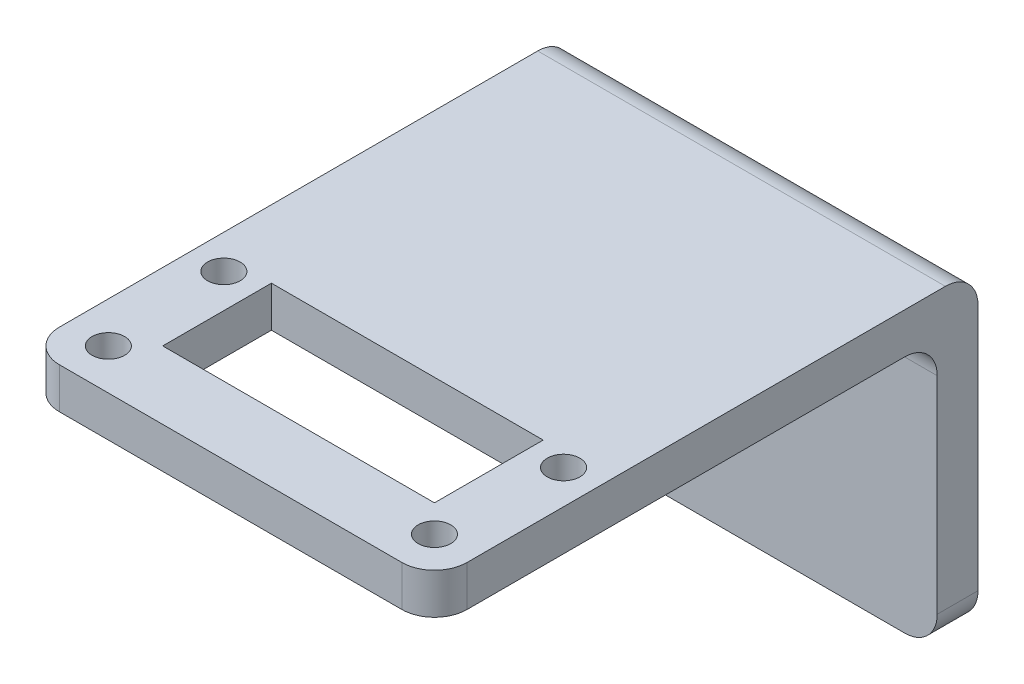
SolidWorks part; units mm, degrees
ref_plane "Plano frontal" through (0, 0, 0) normal (0, 0, 1) x (1, 0, 0)
ref_plane "Plano superior" through (0, 0, 0) normal (0, 1, 0) x (1, 0, 0)
ref_plane "Plano direito" through (0, 0, 0) normal (1, 0, 0) x (0, 0, -1)
sketch "Esboço1" plane through (0, 0, 0) normal (0, 1, 0) x (1, 0, 0)
  line L0 (0, 0) -> (0, 20) construction
  line L1 (-15, 20) -> (15, 20)
  line L2 (0, 0) -> (15, 0) construction
  line L3 (15, -20) -> (15, 20)
  line L4 (-15, 20) -> (-15, -20)
  line L5 (-15, -20) -> (15, -20)
  point P5 (0, 20)
  point P10 (15, 0)
  dimension "D1" = 30
  dimension "D2" = 40
extrude "Ressalto-extrusão1" add sketch "Esboço1" along normal blind 3
sketch "Esboço2" plane through (0, 3, 0) normal (0, 1, 0) x (1, 0, 0)
  line L4 (0, -20) -> (0, 20) construction
  line L5 (-15, -20) -> (15, -20) construction
  line L6 (15, 20) -> (-15, 20) construction
  line L7 (-10, -7) -> (10, -7)
  line L9 (-8.8957, -8) -> (9.1043, -8) construction
  line L10 (10, -7) -> (10, -15)
  line L11 (10, -15) -> (-10, -15)
  line L12 (-10, -15) -> (-10, -7)
  point P3 (0, -7)
  dimension "D1" = 0
  dimension "D2" = 20
  dimension "D3" = 1
  dimension "D4" = 8
extrude "Corte-extrusão1" cut sketch "Esboço2" against normal through all
sketch "Esboço3" plane through (0, 0, 0) normal (0, -1, 0) x (1, 0, 0)
  line L0 (-15, -20) -> (-15, 20) construction
  line L1 (-15, 20) -> (15, 20) construction
  line L2 (15, 20) -> (15, -20) construction
  line L4 (-15.9979, 5) -> (16.0545, 5) construction
  line L5 (54.6527, 5) -> (-54.4441, 5) construction
  circle A0 centre (-12, 17) radius 1.2
  circle A1 centre (12, 17) radius 1.2
  circle A2 centre (-12.5, 8) radius 1.2
  circle A3 centre (12.5, 8) radius 1.2
  dimension "D1" = 2.4
  dimension "D6" = 2.4
  dimension "D7" = 2.4
  dimension "D8" = 2.4
  dimension "D2" = 3
  dimension "D3" = 3
  dimension "D4" = 3
  dimension "D5" = 3
  dimension "D9" = 2.5
  dimension "D10" = 2.5
  dimension "D11" = 3
  dimension "D12" = 3
extrude "Corte-extrusão2" cut sketch "Esboço3" against normal through all
sketch "Esboço4" plane through (0, 0, 0) normal (0, -1, 0) x (1, 0, 0)
  line L0 (-15, -17) -> (15, -17)
  line L4 (-15, 20) -> (-15, -20)
  line L5 (-15, -20) -> (15, -20)
  line L6 (15, -20) -> (15, 20)
  line L7 (15, 20) -> (-15, 20)
  line L8 (-15, 20) -> (-15, -20)
  line L9 (-15, -20) -> (15, -20)
  line L10 (15, -20) -> (15, 20)
  line L11 (15, 20) -> (-15, 20)
  dimension "D2" = 3
  dimension "D1" = 0
extrude "Ressalto-extrusão2" add sketch "Esboço4" along normal blind 20
fillet "Filete5" radius 2.4 1 edges at (0, 0, -17)
fillet "Filete6" radius 2.4 1 edges at (0, 3, -20)
fillet "Filete7" radius 2.4 2 edges at (15, 1.5, 20) (-15, 1.5, 20)
fillet "Filete8" radius 2.4 2 edges at (-15, -20, -18.5) (15, -20, -18.5)
